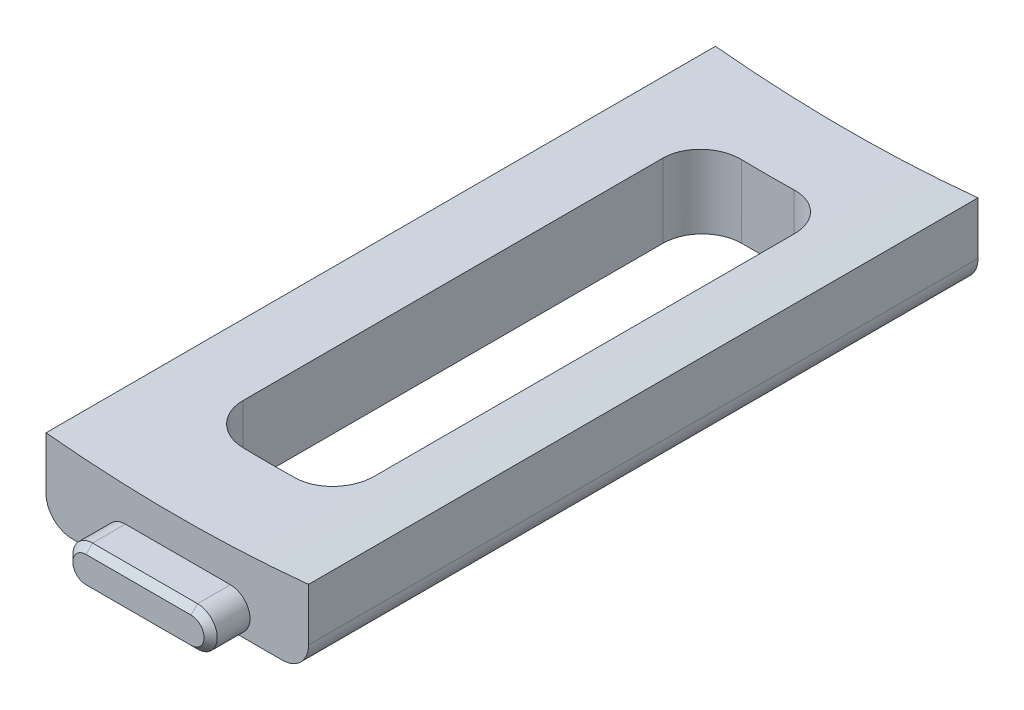
SolidWorks part; units mm, degrees
material "PLA"
ref_plane "前视基准面" through (0, 0, 0) normal (0, 0, 1) x (1, 0, 0)
ref_plane "上视基准面" through (0, 0, 0) normal (0, 1, 0) x (1, 0, 0)
ref_plane "右视基准面" through (0, 0, 0) normal (1, 0, 0) x (0, 0, -1)
sketch "草图1" plane through (0, 0, 0) normal (0, 0, 1) x (1, 0, 0)
  line L0 (-4, 0) -> (4, 0) construction
  line L2 (-4, 1.5) -> (4, 1.5)
  line L3 (-4, -1.5) -> (4, -1.5)
  arc A0 (-4, 1.5) -> (-4, -1.5) centre (-4, 0) ccw
  arc A1 (4, -1.5) -> (4, 1.5) centre (4, 0) ccw
  point P5 (0, 0)
  dimension "D2" = 1.5
  dimension "D1" = 8
extrude "凸台-拉伸1" add sketch "草图1" along normal blind 3
sketch "草图2" plane through (0, 0, 3) normal (0, 0, 1) x (1, 0, 0)
  line L0 (-10, -1.5) -> (10, -1.5)
  line L1 (-4, -1.5) -> (4, -1.5) construction
  line L2 (10, -1.5) -> (10, 4.5013)
  line L3 (-10, -1.5) -> (-10, 4.5013)
  circle A0 centre (0, 104) radius 100
  point P2 (0, -1.5)
  point P8 (0, -1.5)
  arc M2 (-4, 1.5) -> (-4, -1.5) centre (-4, 0) ccw
  line M3 (-4, -1.5) -> (4, -1.5)
  arc M4 (4, -1.5) -> (4, 1.5) centre (4, 0) ccw
  line M5 (4, 1.5) -> (-4, 1.5)
  dimension "D1" = 200
  dimension "D2" = 104
  dimension "D3" = 20
extrude "凸台-拉伸2" add sketch "草图2" along normal blind 51 contours A0 L3 L0 L2 M2 M5 M4 | M5 M2 M3 M4
sketch "草图3" plane through (0, 0, 54) normal (0, 0, 1) x (1, 0, 0)
  line L0 (-3.9547, 0) -> (4.0453, 0) construction
  line L2 (-3.9547, 1.5) -> (4.0453, 1.5)
  line L3 (-3.9547, -1.5) -> (4.0453, -1.5)
  arc A0 (-3.9547, 1.5) -> (-3.9547, -1.5) centre (-3.9547, 0) ccw
  arc A1 (4.0453, -1.5) -> (4.0453, 1.5) centre (4.0453, 0) ccw
  point P5 (0.0453, 0)
  dimension "D2" = 1.5
  dimension "D1" = 8
extrude "凸台-拉伸3" add sketch "草图3" along normal blind 3
fillet "圆角1" radius 2 2 edges at (10, -1.5, 28.5) (-10, -1.5, 28.5)
chamfer "倒角1" distance 0.5 8 edges at (0.0453, 1.5, 57) (5.5453, 0, 57) (0.0453, -1.5, 57) (-5.4547, 0, 57) (0, -1.5, 0) (5.5, 0, 0) (0, 1.5, 0) (-5.5, 0, 0)
sketch "草图4" plane through (0, -1.5, 0) normal (0, -1, 0) x (1, 0, 0)
  line L1 (-5, 47) -> (5, 47)
  line L2 (-5, 47) -> (-5, 9)
  line L3 (-5, 9) -> (5, 9)
  line L4 (5, 47) -> (5, 9)
  line L5 (-5, 47) -> (5, 9) construction
  line L6 (-5, 9) -> (5, 47) construction
  point P0 (0, 28)
  dimension "D1" = 38
  dimension "D2" = 10
  dimension "D3" = 28
extrude "切除-拉伸1" cut sketch "草图4" against normal through all
fillet "圆角2" radius 3 4 edges at (5, 1.3125, 9) (-5, 1.3125, 9) (-5, 1.3125, 47) (5, 1.3125, 47)
